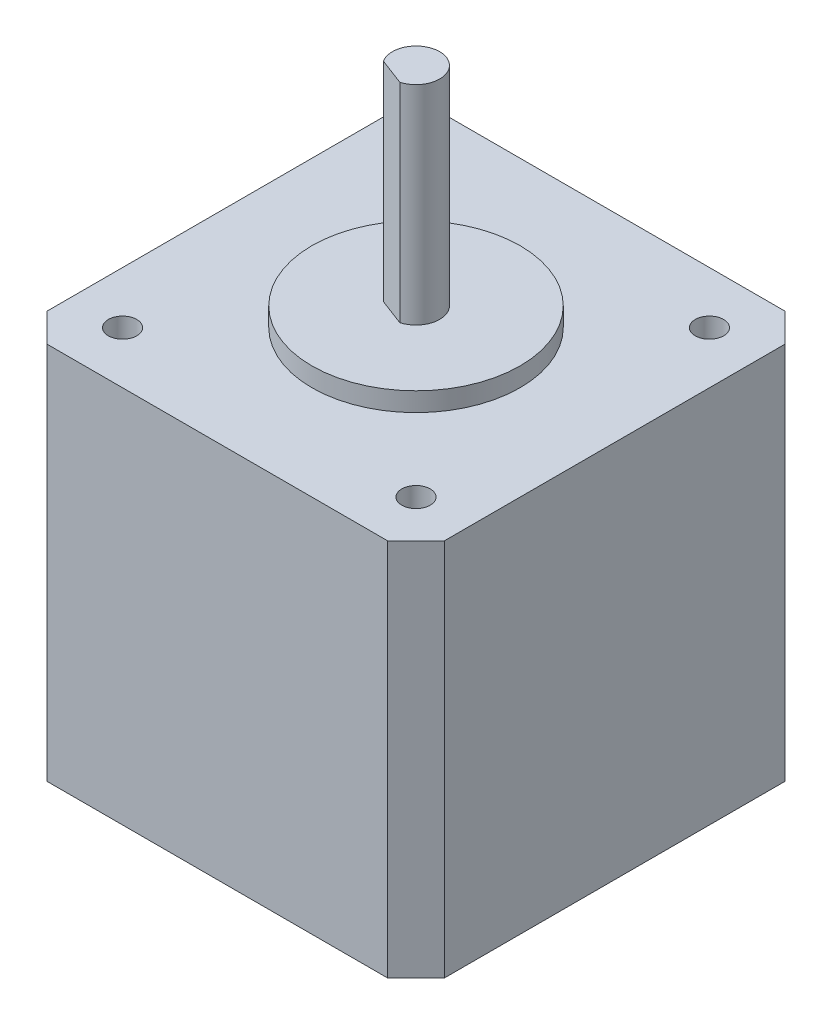
SolidWorks part; units mm, degrees
ref_plane "Front Plane" through (0, 0, 0) normal (0, 0, 1) x (1, 0, 0)
ref_plane "Top Plane" through (0, 0, 0) normal (0, 1, 0) x (1, 0, 0)
ref_plane "Right Plane" through (0, 0, 0) normal (1, 0, 0) x (0, 0, -1)
sketch "Sketch1" plane through (0, 0, 0) normal (0, 1, 0) x (1, 0, 0)
  line L1 (0, 0) -> (42, 0)
  line L2 (0, 0) -> (0, 42)
  line L3 (0, 42) -> (42, 42)
  line L4 (42, 0) -> (42, 42)
  dimension "D1" = 42
  dimension "D2" = 42
extrude "Boss-Extrude1" add sketch "Sketch1" along normal blind 40
chamfer "Chamfer1" distance 3 angle 45 4 edges at (42, 20, -42) (0, 20, -42) (42, 20, 0) (0, 20, 0)
sketch "Sketch2" plane through (0, 40, 0) normal (0, 1, 0) x (1, 0, 0)
  line L0 (42, 21) -> (0, 21) construction
  line L1 (42, 3) -> (42, 39) construction
  line L2 (0, 39) -> (0, 3) construction
  circle A0 centre (21, 21) radius 11
  dimension "D1" = 22
extrude "Boss-Extrude2" add sketch "Sketch2" along normal blind 2
sketch "Sketch3" plane through (0, 42, 0) normal (0, 1, 0) x (1, 0, 0)
  circle A0 centre (21, 21) radius 2.5
  dimension "D1" = 5
extrude "Boss-Extrude3" add sketch "Sketch3" along normal blind 22
sketch "Sketch4" plane through (0, 64, 0) normal (0, 1, 0) x (1, 0, 0)
  line L0 (21.6896, 18.597) -> (18.8862, 19.6651)
  circle A0 centre (21, 21) radius 2.5 construction
  point P4 (20.2879, 19.1311)
  dimension "D1" = 2
extrude "Cut-Extrude1" cut sketch "Sketch4" against normal blind 22 and the other way through all
sketch "Sketch5" plane through (0, 40, 0) normal (0, 1, 0) x (1, 0, 0)
  line L0 (42, 21) -> (0, 21) construction
  line L1 (42, 3) -> (42, 39) construction
  line L2 (0, 39) -> (0, 3) construction
  line L4 (3, 0) -> (39, 0) construction
  line L5 (21, 0) -> (21, 42) construction
  line L6 (39, 42) -> (3, 42) construction
  line L7 (36.5, 36.5) -> (5.5, 36.5)
  line L8 (36.5, 36.5) -> (36.5, 5.5)
  line L9 (36.5, 5.5) -> (5.5, 5.5)
  line L10 (5.5, 36.5) -> (5.5, 5.5)
  circle A0 centre (36.5, 36.5) radius 1.5
  circle A1 centre (36.5, 5.5) radius 1.5
  circle A2 centre (5.5, 5.5) radius 1.5
  circle A3 centre (5.5, 36.5) radius 1.5
  dimension "D5" = 3
  dimension "D6" = 3
  dimension "D7" = 3
  dimension "D8" = 3
  dimension "D1" = 31
  dimension "D2" = 31
  dimension "D3" = 15.5
  dimension "D4" = 15.5
extrude "Cut-Extrude2" cut sketch "Sketch5" against normal blind 10 contours A3 | A0 | A1 | A2
